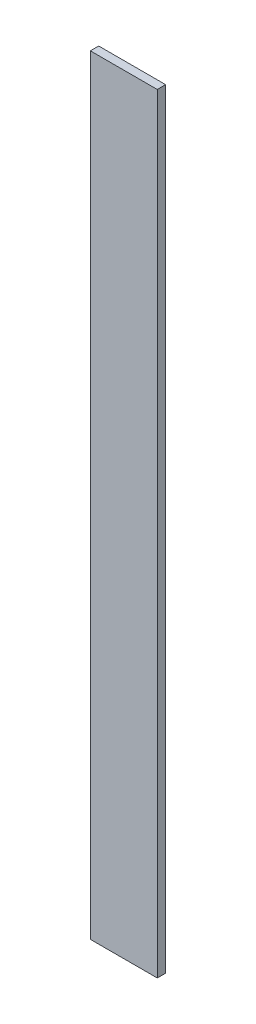
SolidWorks part; units mm, degrees
material "Pin"
ref_plane "Front" through (0, 0, 0) normal (0, 0, 1) x (1, 0, 0)
ref_plane "Top" through (0, 0, 0) normal (0, 1, 0) x (1, 0, 0)
ref_plane "Right" through (0, 0, 0) normal (1, 0, 0) x (0, 0, -1)
sketch "Esquisse1" plane through (0, 0, 0) normal (0, 0, 1) x (1, 0, 0)
  line L1 (-25.4, 292.1) -> (25.4, 292.1)
  line L2 (-25.4, 292.1) -> (-25.4, -292.1)
  line L3 (-25.4, -292.1) -> (25.4, -292.1)
  line L4 (25.4, 292.1) -> (25.4, -292.1)
  line L5 (-25.4, 292.1) -> (25.4, -292.1) construction
  line L6 (-25.4, -292.1) -> (25.4, 292.1) construction
  point P0 (0, 0)
  dimension "D1" = 584.2
  dimension "D2" = 50.8
extrude "Boss.-Extru.1" add sketch "Esquisse1" along normal blind 6.35
